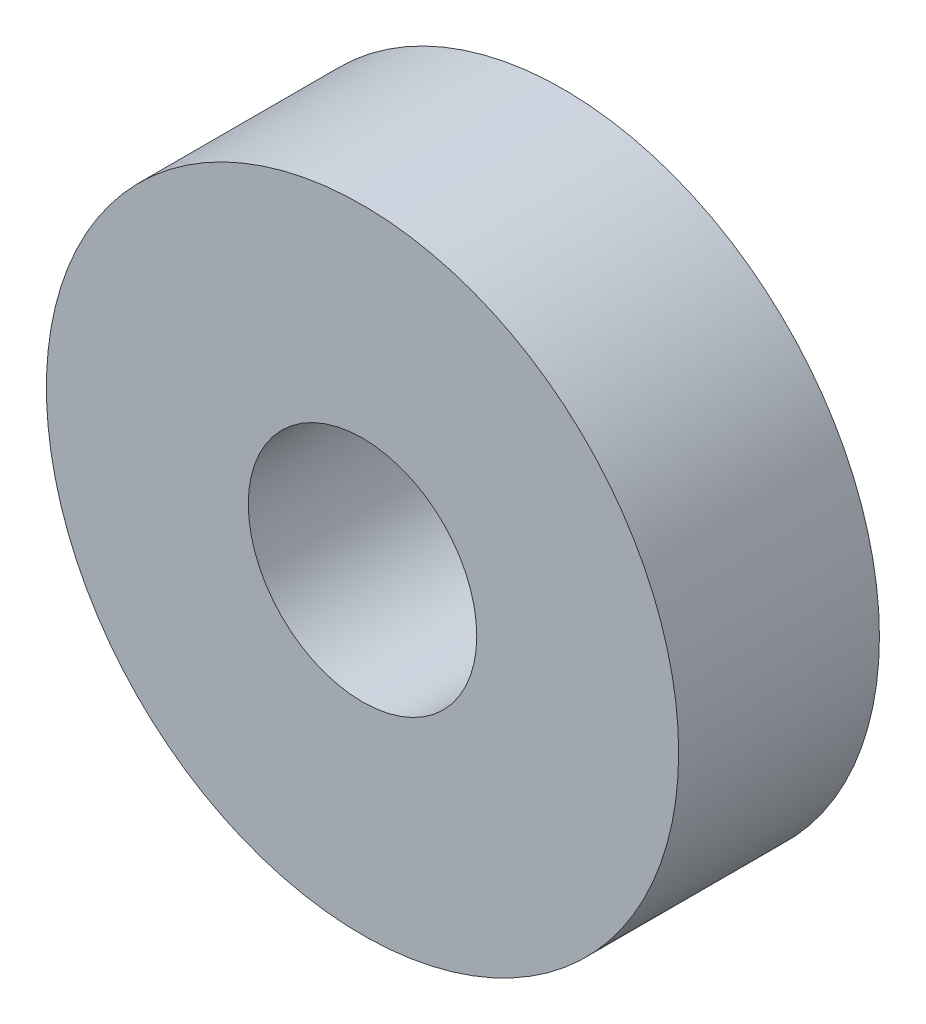
SolidWorks part; units mm, degrees
material "Chrome Stainless Steel"
ref_plane "Front Plane" through (0, 0, 0) normal (0, 0, 1) x (1, 0, 0)
ref_plane "Top Plane" through (0, 0, 0) normal (0, 1, 0) x (1, 0, 0)
ref_plane "Right Plane" through (0, 0, 0) normal (1, 0, 0) x (0, 0, -1)
sketch "Sketch1" plane through (0, 0, 0) normal (0, 0, 1) x (1, 0, 0)
  circle A0 centre (0, 0) radius 3.9751
  circle A1 centre (0, 0) radius 10.9982
  dimension "D1" = 21.9964
  dimension "D2" = 7.9502
extrude "Boss-Extrude1" add sketch "Sketch1" along normal blind 6.985
